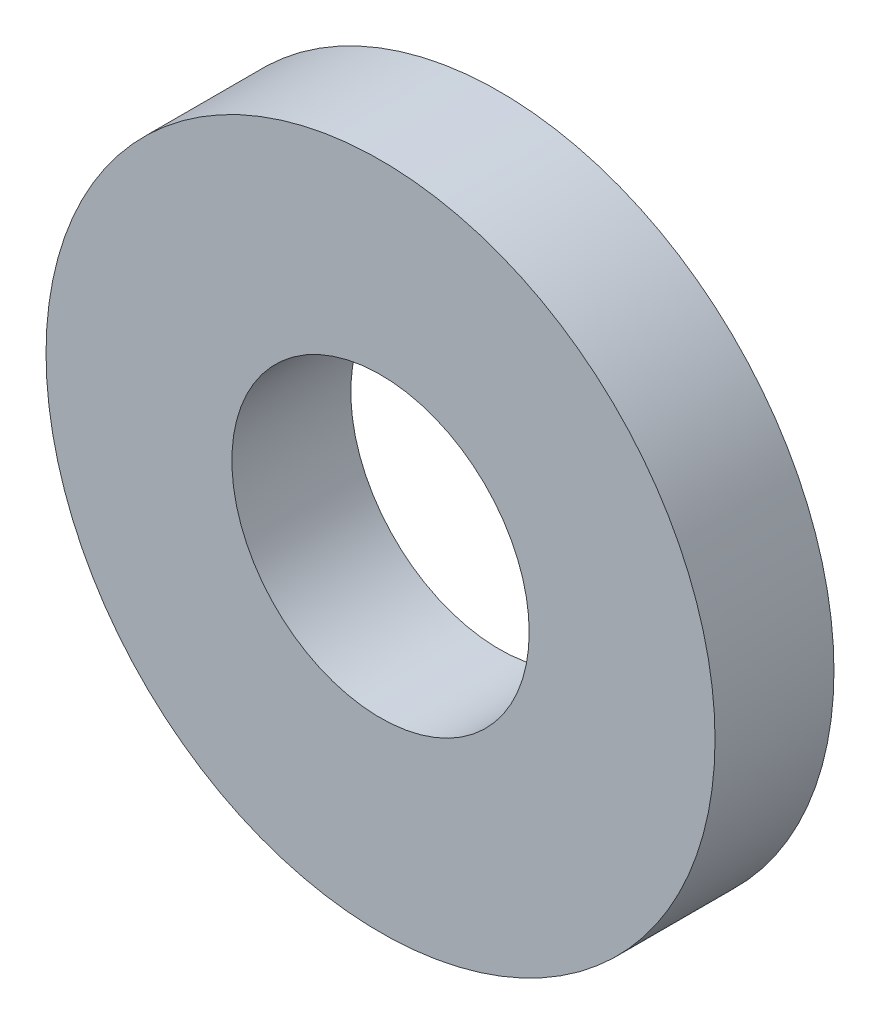
SolidWorks part; units mm, degrees
ref_plane "Ön Düzlem" through (0, 0, 0) normal (0, 0, 1) x (1, 0, 0)
ref_plane "Üst Düzlem" through (0, 0, 0) normal (0, 1, 0) x (1, 0, 0)
ref_plane "Sağ Düzlem" through (0, 0, 0) normal (1, 0, 0) x (0, 0, -1)
sketch "Çizim1" plane through (0, 0, 0) normal (0, 0, 1) x (1, 0, 0)
  circle A0 centre (0, 0) radius 22.5
  circle A1 centre (0, 0) radius 10
  dimension "D1" = 45
  dimension "D2" = 20
extrude "Yükseklik-Ekstrüzyon1" add sketch "Çizim1" along normal blind 8
